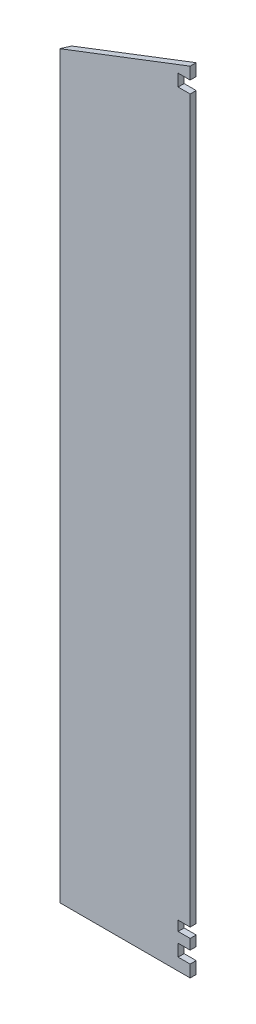
SolidWorks part; units mm, degrees
ref_plane "Front Plane" through (0, 0, 0) normal (0, 0, 1) x (1, 0, 0)
ref_plane "Top Plane" through (0, 0, 0) normal (0, 1, 0) x (1, 0, 0)
ref_plane "Right Plane" through (0, 0, 0) normal (1, 0, 0) x (0, 0, -1)
sketch "Sketch1" plane through (0, 0, 0) normal (0, 0, 1) x (1, 0, 0)
  line L0 (173, 1048.1) -> (-173, 915.283)
  line L1 (-173, -1048.1) -> (173, -1048.1) construction
  line L2 (-173, -1048.1) -> (-173, 1048.1) construction
  line L3 (-173, 1048.1) -> (173, 1048.1) construction
  line L4 (173, -1048.1) -> (173, 1048.1) construction
  line L5 (-173, -1048.1) -> (173, 1048.1) construction
  line L6 (-173, 1048.1) -> (173, -1048.1) construction
  line L7 (-173, 915.283) -> (-173, -1048.1)
  line L8 (-173, -1048.1) -> (173, -1048.1)
  line L9 (173, -1048.1) -> (173, 1048.1)
  line L10 (-157, 921.4249) -> (-157, -1048.1) construction
  point P0 (0, 0)
  dimension "D1" = 346
  dimension "D2" = 2096.2
  dimension "D3" = 69
  dimension "D4" = 1963.383
  dimension "D5" = 16
  dimension "D6" = 1969.5249
extrude "Boss-Extrude1" add sketch "Sketch1" along normal blind 16
sketch "Sketch2" plane through (0, -1048.1, 0) normal (0, -1, 0) x (1, 0, 0)
  line L0 (-173, 16) -> (-157, 16)
  line L1 (-173, 16) -> (173, 16) construction
  line L2 (-157, 16) -> (-173, 0)
  line L3 (-173, 0) -> (-173, 16)
  dimension "D1" = 45
extrude "Cut-Extrude1" [suppressed] cut sketch "Sketch2" against normal through all
sketch "Sketch3" plane through (0, -1048.1, 0) normal (0, -1, 0) x (1, 0, 0)
  line L0 (-173, 16) -> (-157, 0)
  line L1 (-173, 0) -> (173, 0) construction
  line L2 (-157, 0) -> (-173, 0)
  line L3 (-173, 0) -> (-173, 16)
  dimension "D1" = 45
extrude "Cut-Extrude2" cut sketch "Sketch3" against normal through all
sketch "Sketch4" plane through (-328.4399, 855.6152, 0) normal (-0.3584, 0.9336, 0) x (0.9336, 0.3584, 0)
  line L0 (166.4987, -16) -> (537.1149, -16) construction
  dimension "D1" = 370.6162
sketch "Sketch5" [suppressed] plane through (173, 0, 0) normal (1, 0, 0) x (0, 0, -1)
  line L0 (-16, -1048.1) -> (0, -1048.1) construction
  line L1 (-16, 1048.1) -> (-8, 1048.1)
  line L2 (-16, 1048.1) -> (-16, -1048.1)
  line L3 (-16, -1048.1) -> (-8, -1048.1)
  line L4 (-8, 1048.1) -> (-8, -1048.1)
  dimension "D1" = 8
extrude "Cut-Extrude3" [suppressed] cut sketch "Sketch5" against normal blind 32
sketch "Sketch6" plane through (0, 0, 16) normal (0, 0, 1) x (1, 0, 0)
  line L0 (173, -1048.1) -> (173, 1048.1) construction
  line L1 (173, 1016.1) -> (141, 1016.1)
  line L2 (173, 1016.1) -> (173, 984.1)
  line L3 (173, 984.1) -> (141, 984.1)
  line L4 (141, 1016.1) -> (141, 984.1)
  line L5 (-173, -1048.1) -> (173, -1048.1) construction
  line L6 (173, -984.1) -> (141, -984.1)
  line L7 (173, -984.1) -> (173, -1016.1)
  line L8 (173, -1016.1) -> (141, -1016.1)
  line L9 (141, -984.1) -> (141, -1016.1)
  line L10 (173, -957.1) -> (141, -957.1)
  line L11 (141, -957.1) -> (141, -931.1)
  line L12 (141, -931.1) -> (173, -931.1)
  line L13 (173, -931.1) -> (173, -957.1)
  dimension "D1" = 32
  dimension "D2" = 32
  dimension "D3" = 32
  dimension "D4" = 32
  dimension "D5" = 32
  dimension "D6" = 32
  dimension "D7" = 27
  dimension "D8" = 26
extrude "Cut-Extrude4" cut sketch "Sketch6" against normal through all
